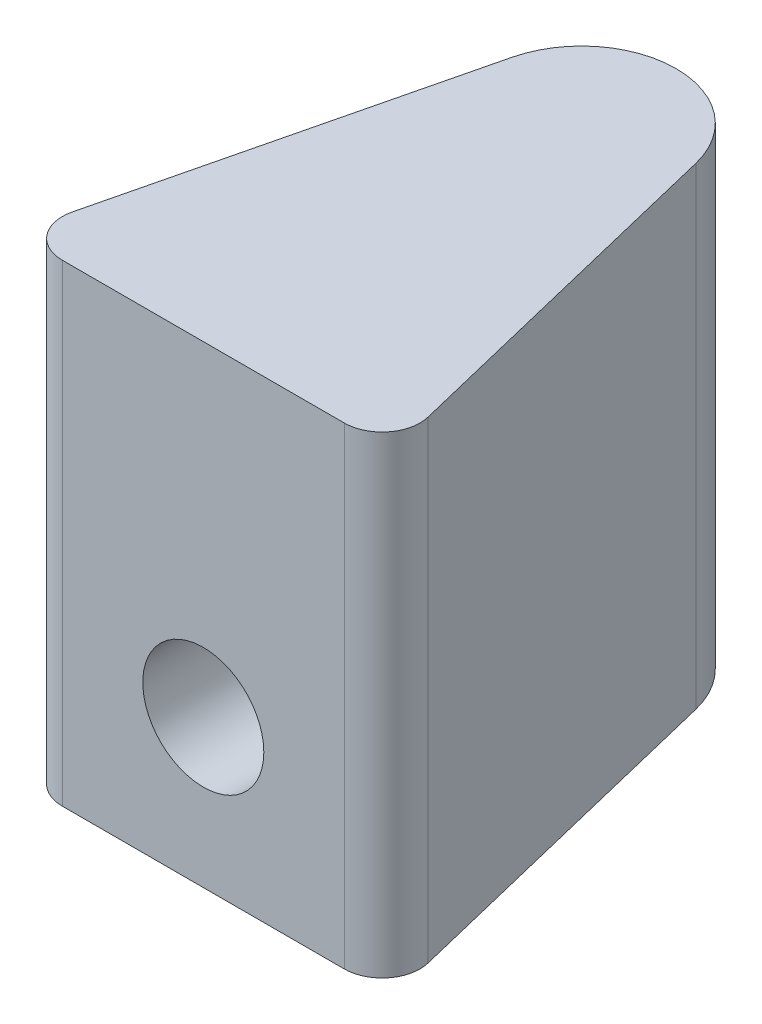
SolidWorks part; units mm, degrees
ref_plane "Alzado" through (0, 0, 0) normal (0, 0, 1) x (1, 0, 0)
ref_plane "Planta" through (0, 0, 0) normal (0, 1, 0) x (1, 0, 0)
ref_plane "Vista lateral" through (0, 0, 0) normal (1, 0, 0) x (0, 0, -1)
sketch "Croquis1" plane through (0, 0, 0) normal (0, 1, 0) x (1, 0, 0)
  line L0 (-4.8589, 1.1794) -> (-10, -20)
  line L1 (-10, -20) -> (10, -20)
  line L2 (10, -20) -> (4.8589, 1.1794)
  line L3 (0, -55) -> (0, 55) construction
  arc A0 (4.8589, 1.1794) -> (-4.8589, 1.1794) centre (0, 0) ccw
  point P1 (0, -20)
  dimension "D1" = 5
  dimension "D2" = 20
  dimension "D3" = 20
extrude "Saliente-Extruir1" add sketch "Croquis1" along normal blind 25
sketch "Croquis2" plane through (0, 0, 20) normal (0, 0, 1) x (1, 0, 0)
  line L0 (0, -13.75) -> (0, 13.75) construction
  line L1 (11, 0) -> (-11, 0) construction
  circle A0 centre (0, 7.8) radius 3.2
  dimension "D1" = 6.4
  dimension "D2" = 7.8
extrude "Cortar-Extruir1" cut sketch "Croquis2" against normal blind 12
fillet "Redondeo1" radius 2 2 edges at (10, 12.5, 20) (-10, 12.5, 20)
